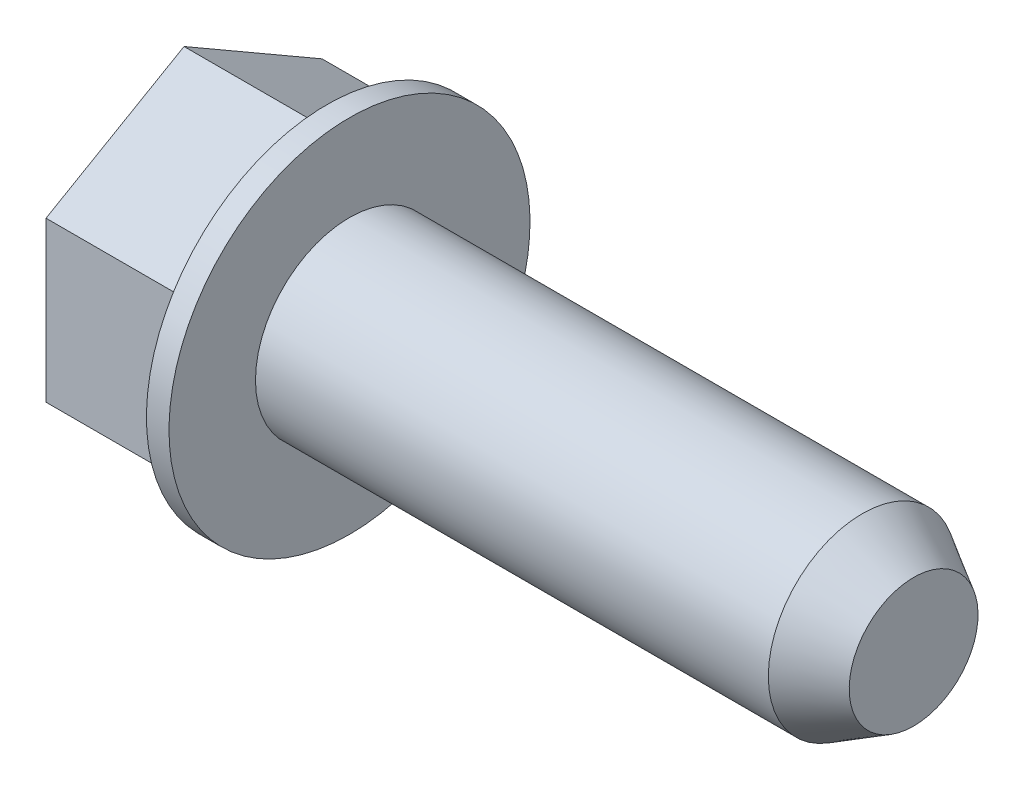
SolidWorks part; units mm, degrees
material "Plain Carbon Steel"
ref_plane "Front Plane" through (0, 0, 0) normal (0, 0, 1) x (1, 0, 0)
ref_plane "Top Plane" through (0, 0, 0) normal (0, 1, 0) x (1, 0, 0)
ref_plane "Right Plane" through (0, 0, 0) normal (1, 0, 0) x (0, 0, -1)
sketch "Sketch1" plane through (0, 0, 0) normal (0, 0, 1) x (1, 0, 0)
  line L0 (4.6228, 0) -> (23.6728, 0) construction
  line L1 (4.6228, 6.096) -> (3.8608, 6.096)
  line L2 (4.6228, 3.175) -> (4.6228, 6.096)
  line L3 (4.6228, 3.175) -> (23.6728, 3.175)
  line L4 (23.6728, 3.175) -> (6.4262, 3.175) construction
  line L5 (23.6728, 3.175) -> (23.6728, 0)
  line L6 (4.6228, 0) -> (23.6728, 0)
  line L7 (3.8608, 6.096) -> (3.8608, 4.6609)
  line L8 (4.6228, 0) -> (0, 0) construction
  line L9 (4.6228, 0) -> (0, 0)
  line L10 (3.8608, 4.6609) -> (-0.9652, 4.6609)
  line L11 (-0.9652, 4.6609) -> (-0.9652, 0)
  line L15 (-0.9652, 0) -> (0, 0)
  dimension "D1" = 19.05
  dimension "D2" = 6.35
  dimension "D3" = 1.8034
  dimension "D4" = 12.192
  dimension "D5" = 0.762
  dimension "D6" = 9.3218
  dimension "D7" = 4.826
  dimension "D10" = 0.9652
revolve "Revolve1" add sketch "Sketch1" angle 360 about L6
cosmetic thread "Cosmetic Thread1" parameters "D1"=19.0499, "D2"=4.8387
sketch "Sketch2" plane through (3.8608, 0, 0) normal (-1, 0, 0) x (0, 0, 1)
  line L13 (0, 5.3819) -> (-4.6609, 2.691)
  line L14 (-4.6609, 2.691) -> (-4.6609, -2.691)
  line L15 (-4.6609, -2.691) -> (0, -5.3819)
  line L16 (0, -5.3819) -> (4.6609, -2.691)
  line L17 (4.6609, -2.691) -> (4.6609, 2.691)
  line L18 (4.6609, 2.691) -> (0, 5.3819)
  circle A4 centre (0, 0) radius 4.6609 construction
  dimension "D2" = 9.3218
extrude "Boss-Extrude1" add sketch "Sketch2" along normal up to surface (4.826 mm away) up to face at (-0.9652, -4.6609, 0)
sketch "Sketch3" plane through (-0.9652, 0, 0) normal (-1, 0, 0) x (0, 0, 1)
  circle A0 centre (0, 0) radius 3.7287
  dimension "D1" = 7.4574
extrude "Cut-Extrude1" cut sketch "Sketch3" against normal blind 0.9652
chamfer "Chamfer1" distance 1 angle 60 1 edges at (23.6728, -3.175, 0)
